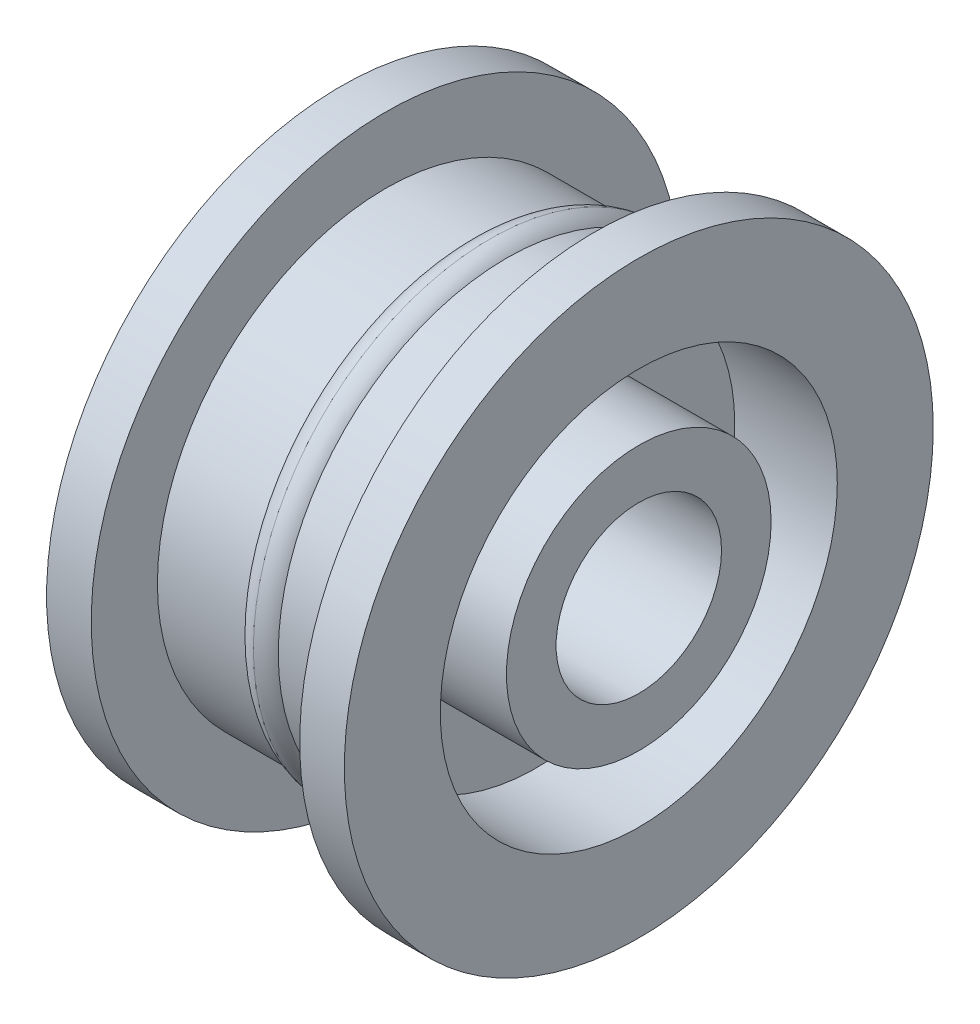
SolidWorks part; units mm, degrees
ref_plane "Спереди" through (0, 0, 0) normal (0, 0, 1) x (1, 0, 0)
ref_plane "Сверху" through (0, 0, 0) normal (0, 1, 0) x (1, 0, 0)
ref_plane "Справа" through (0, 0, 0) normal (1, 0, 0) x (0, 0, -1)
sketch "Эскиз1" plane through (0, 0, 0) normal (0, 0, 1) x (1, 0, 0)
  line L0 (-9, 5) -> (9, 5)
  line L1 (9, 5) -> (9, 8)
  line L2 (9, 8) -> (2.8, 8)
  line L3 (2.8, 8) -> (2.8, 12)
  line L4 (2.8, 12) -> (9, 12)
  line L5 (9, 12) -> (9, 17.8)
  line L6 (9, 17.8) -> (6.3, 17.8)
  line L7 (6.3, 17.8) -> (6.3, 13.8)
  line L8 (6.3, 13.8) -> (1.3, 13.8)
  line L9 (0, 0) -> (0, 21.8597) construction
  line L10 (-6.3, 13.8) -> (-1.3, 13.8)
  line L11 (-6.3, 17.8) -> (-6.3, 13.8)
  line L12 (-9, 17.8) -> (-6.3, 17.8)
  line L13 (-9, 12) -> (-9, 17.8)
  line L14 (-2.8, 12) -> (-9, 12)
  line L15 (-2.8, 8) -> (-2.8, 12)
  line L16 (-9, 8) -> (-2.8, 8)
  line L17 (-9, 5) -> (-9, 8)
  line L18 (0, 0) -> (-19.7296, 0) construction
  line L19 (-1.3, 13.8) -> (1.3, 13.8)
  point P21 (0, 5)
  point P25 (0, 5)
  dimension "D9" = 4
  dimension "D1" = 9
  dimension "D2" = 3
  dimension "D3" = 5
  dimension "D4" = 6.2
  dimension "D5" = 4
  dimension "D6" = 17.8
  dimension "D7" = 2.7
revolve "Повернуть1" add sketch "Эскиз1" angle 360 about L18
sketch "Эскиз2" plane through (0, 0, 0) normal (0, 0, 1) x (1, 0, 0)
  line L0 (-1.3, 13.3) -> (1.3, 13.3)
  line L1 (16.7042, 17.6258) -> (16.89, 17.7703)
  line L2 (0, 0) -> (19.9255, 0) construction
  arc A2 (1.3, 13.3) -> (0, 14.3) centre (-0.1158, 12.8045) ccw
  arc A3 (0, 14.3) -> (-1.3, 13.3) centre (0.1158, 12.8045) ccw
  dimension "D1" = 1.5
  dimension "D2" = 0.1158
  dimension "D3" = 1.3
  dimension "D4" = 16.7042
  dimension "D5" = 16.89
  dimension "D6" = 12.8045
  dimension "D7" = 1.3
  dimension "D10" = 17.6258
  dimension "D11" = 17.7703
revolve "Повернуть2" add sketch "Эскиз2" angle 360 about L2
